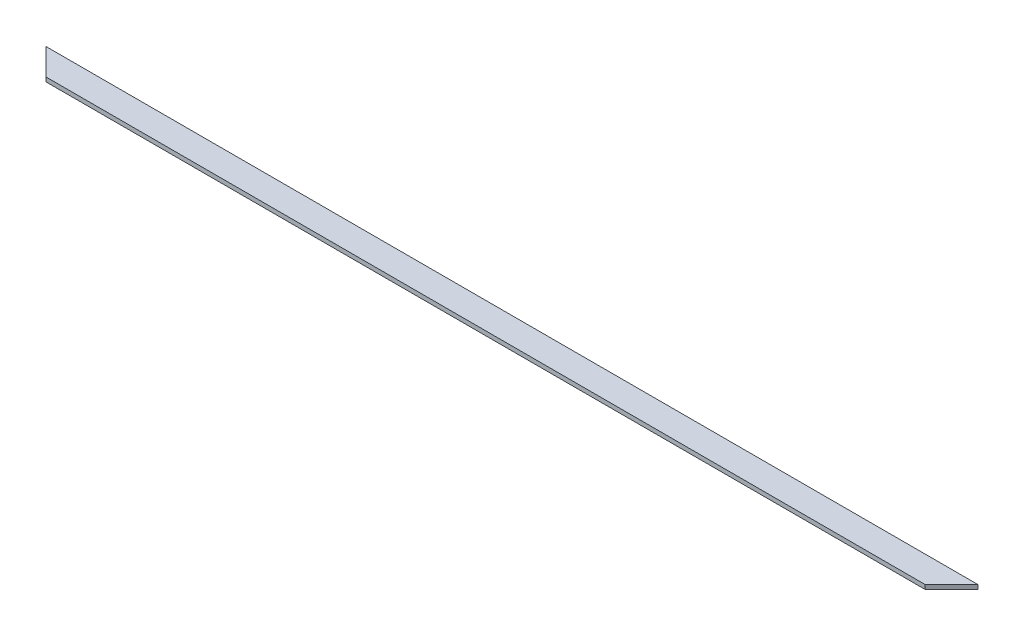
SolidWorks part; units mm, degrees
material "PE High Density"
ref_plane "Front Plane" through (0, 0, 0) normal (0, 0, 1) x (1, 0, 0)
ref_plane "Top Plane" through (0, 0, 0) normal (0, 1, 0) x (1, 0, 0)
ref_plane "Right Plane" through (0, 0, 0) normal (1, 0, 0) x (0, 0, -1)
sketch "Sketch1" plane through (0, 0, 0) normal (0, 1, 0) x (1, 0, 0)
  line L0 (-1348.5003, 921.398) -> (-1348.5003, 788.048) construction
  line L1 (-1481.8503, 921.398) -> (3228.2622, 921.398)
  line L2 (3094.9122, 921.398) -> (3094.9122, 788.048) construction
  line L3 (-1348.5003, 788.048) -> (3094.9122, 788.048)
  line L5 (-1481.8503, 921.398) -> (-1348.5003, 788.048)
  line L6 (3228.2622, 921.398) -> (3094.9122, 788.048)
  dimension "D1" = 4710.1125
  dimension "D2" = 133.35
  dimension "D3" = 133.35
extrude "Boss-Extrude1" add sketch "Sketch1" along normal blind 21.59 contours L3 L6 L1 L5
